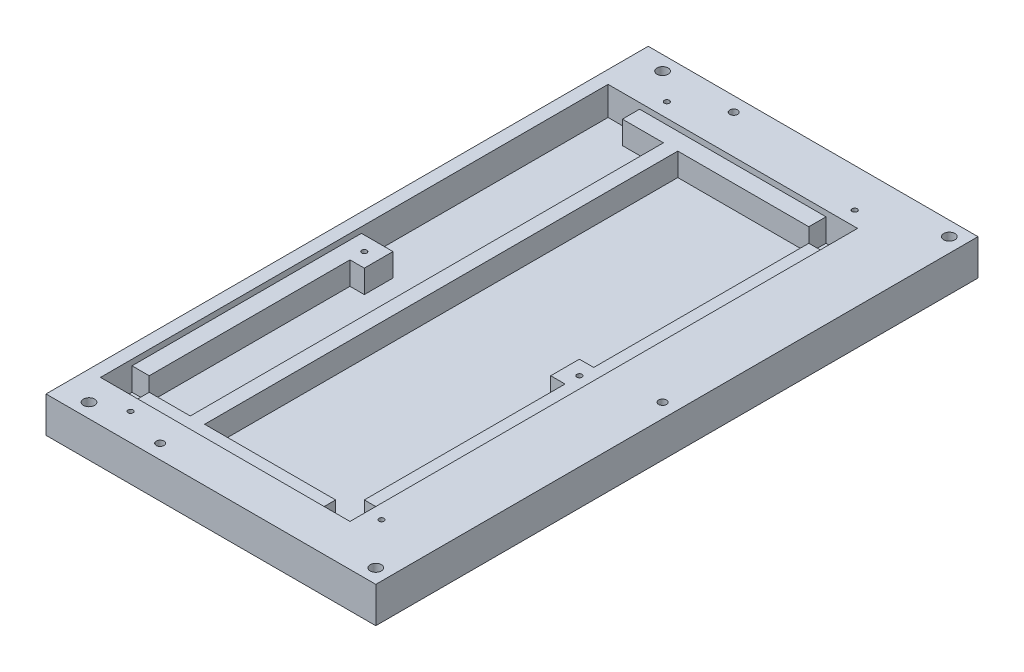
SolidWorks part; units mm, degrees
ref_plane "Front Plane" through (0, 0, 0) normal (0, 0, 1) x (1, 0, 0)
ref_plane "Top Plane" through (0, 0, 0) normal (0, 1, 0) x (1, 0, 0)
ref_plane "Right Plane" through (0, 0, 0) normal (1, 0, 0) x (0, 0, -1)
sketch "Sketch1" plane through (0, 0, 0) normal (0, 1, 0) x (1, 0, 0)
  line L1 (0, 0) -> (146.05, 0)
  line L2 (0, 0) -> (0, 266.7)
  line L3 (0, 266.7) -> (146.05, 266.7)
  line L4 (146.05, 0) -> (146.05, 266.7)
  dimension "D1" = 266.7
  dimension "D2" = 146.05
extrude "Boss-Extrude1" add sketch "Sketch1" along normal blind 15.875
sketch "Sketch2" plane through (0, 15.875, 0) normal (0, 1, 0) x (1, 0, 0)
  line L1 (5.715, 243.205) -> (116.205, 243.205)
  line L2 (5.715, 243.205) -> (5.715, 18.415)
  line L3 (5.715, 18.415) -> (116.205, 18.415)
  line L4 (116.205, 243.205) -> (116.205, 18.415)
  line L5 (0, 0) -> (146.05, 0) construction
  line L6 (0, 266.7) -> (0, 0) construction
  dimension "D1" = 224.79
  dimension "D2" = 110.49
  dimension "D3" = 5.715
  dimension "D4" = 18.415
extrude "Cut-Extrude1" cut sketch "Sketch2" against normal blind 2.54
sketch "Sketch3" plane through (0, 13.335, 0) normal (0, 1, 0) x (1, 0, 0)
  line L0 (19.685, 26.035) -> (19.685, 18.415)
  line L1 (19.685, 243.205) -> (19.685, 235.585)
  line L2 (19.685, 235.585) -> (37.8587, 235.585)
  line L3 (44.2087, 26.035) -> (102.235, 26.035)
  line L4 (102.235, 26.035) -> (102.235, 18.415)
  line L5 (44.2087, 235.585) -> (102.235, 235.585)
  line L6 (108.585, 32.385) -> (108.585, 121.285)
  line L7 (102.235, 235.585) -> (102.235, 243.205)
  line L8 (108.585, 121.285) -> (102.235, 121.285)
  line L9 (102.235, 121.285) -> (102.235, 133.985)
  line L10 (102.235, 133.985) -> (108.585, 133.985)
  line L11 (108.585, 133.985) -> (108.585, 229.235)
  line L12 (102.235, 243.205) -> (116.205, 243.205)
  line L13 (116.205, 243.205) -> (5.715, 243.205) construction
  line L14 (102.235, 18.415) -> (116.205, 18.415)
  line L15 (116.205, 18.415) -> (116.205, 32.385)
  line L16 (116.205, 18.415) -> (116.205, 243.205) construction
  line L17 (116.205, 32.385) -> (108.585, 32.385)
  line L18 (19.685, 243.205) -> (5.715, 243.205)
  line L19 (5.715, 243.205) -> (5.715, 18.415) construction
  line L20 (5.715, 243.205) -> (5.715, 133.985)
  line L22 (19.685, 18.415) -> (5.715, 18.415)
  line L23 (5.715, 243.205) -> (5.715, 18.415) construction
  line L24 (13.335, 121.285) -> (13.335, 32.385)
  line L25 (5.715, 18.415) -> (5.715, 32.385)
  line L26 (19.685, 26.035) -> (37.8587, 26.035)
  line L27 (37.8587, 235.585) -> (37.8587, 26.035)
  line L28 (116.205, 243.205) -> (116.205, 229.235)
  line L29 (44.2087, 26.035) -> (44.2087, 235.585)
  line L30 (116.205, 229.235) -> (108.585, 229.235)
  line L31 (5.715, 18.415) -> (116.205, 18.415) construction
  line L32 (5.715, 18.415) -> (116.205, 18.415) construction
  line L33 (5.715, 32.385) -> (13.335, 32.385)
  line L34 (5.715, 133.985) -> (19.685, 133.985)
  line L35 (116.205, 18.415) -> (116.205, 243.205) construction
  line L36 (19.685, 133.985) -> (19.685, 121.285)
  line L37 (19.685, 121.285) -> (13.335, 121.285)
  dimension "D3" = 7.62
  dimension "D4" = 13.97
  dimension "D5" = 6.35
  dimension "D6" = 13.97
  dimension "D7" = 13.97
  dimension "D8" = 13.97
  dimension "D9" = 12.7
  dimension "D10" = 12.7
  dimension "D11" = 88.9
  dimension "D12" = 18.1737
  dimension "D13" = 13.97
  dimension "D14" = 58.0263
  dimension "D15" = 13.97
  dimension "D16" = 6.35
  dimension "D17" = 7.62
  dimension "D18" = 7.62
  dimension "D19" = 7.62
  dimension "D20" = 6.35
  dimension "D21" = 6.35
  dimension "D22" = 13.97
  dimension "D23" = 88.9
  dimension "D24" = 7.62
  dimension "D25" = 7.62
  dimension "D26" = 209.55
  dimension "D27" = 95.25
extrude "Cut-Extrude2" cut sketch "Sketch3" against normal blind 10.16
hole_wizard "#4-40 Tapped Hole1" positions "Sketch5" profile "Sketch4" tap size "#4-40" standard "ANSI Inch"
sketch "Sketch5" plane through (0, 13.335, 0) normal (0, 1, 0) x (1, 0, 0)
  line L2 (102.235, 121.285) -> (102.235, 133.985) construction
  line L17 (108.585, 121.285) -> (102.235, 121.285) construction
  line L18 (19.685, 121.285) -> (13.335, 121.285) construction
  line L19 (19.685, 133.985) -> (19.685, 121.285) construction
  point P2 (108.585, 127.635)
  point P53 (13.335, 127.635)
  point P56 (16.51, 121.285)
  dimension "D1" = 6.35
  dimension "D2" = 6.35
  dimension "D3" = 6.35
  dimension "D4" = 6.35
sketch "Sketch4" plane through (108.585, 13.335, -127.635) normal (1, 0, 0) x (0, 0, 1)
  line L0 (0, 0) -> (0, 10.8392)
  line L1 (0, 10.8392) -> (1.1303, 10.16)
  line L2 (1.1303, 10.16) -> (1.1303, 0)
  line L5 (1.1303, 0) -> (0, 0)
  line L10 (0, 10.8392) -> (-1.1303, 10.16) construction
  line L11 (0, -6.35) -> (0, 107.95) construction
  dimension "Tap Drill Dia." = 2.2606
  dimension "Tap Drill Depth" = 10.16
  dimension "Drill Angle" = 118
cosmetic thread "Hole Thread5" parameters "D1"=5.6896, "D2"=2.8448
cosmetic thread "Hole Thread14" parameters "D1"=5.6896, "D2"=2.8448
hole_wizard "#8 Clearance Hole1" positions "Sketch9" profile "Sketch8" hole size "#8" standard "ANSI Inch" end condition through all
sketch "Sketch9" plane through (0, 15.875, 0) normal (0, 1, 0) x (1, 0, 0)
  line L0 (0, 0) -> (146.05, 0) construction
  line L1 (146.05, 0) -> (146.05, 266.7) construction
  line L2 (146.05, 266.7) -> (0, 266.7) construction
  line L3 (0, 266.7) -> (0, 0) construction
  point P0 (12.7, 6.35)
  point P2 (139.7, 6.35)
  point P4 (139.7, 260.35)
  point P6 (12.7, 260.35)
  dimension "D1" = 6.35
  dimension "D2" = 6.35
  dimension "D3" = 6.35
  dimension "D4" = 6.35
  dimension "D5" = 6.35
  dimension "D6" = 6.35
  dimension "D7" = 12.7
  dimension "D8" = 12.7
sketch "Sketch8" plane through (12.7, 15.875, -6.35) normal (1, 0, 0) x (0, 0, 1)
  line L0 (0, 0) -> (0, 15.875)
  line L1 (0, 15.875) -> (2.4574, 15.875)
  line L2 (2.4574, 15.875) -> (2.4574, 0)
  line L5 (2.4574, 0) -> (0, 0)
  line L11 (0, -6.35) -> (0, 107.95) construction
  dimension "Thru Hole Dia." = 4.9149
  dimension "Thru Hole Depth" = 15.875
hole_wizard "#8-32 Tapped Hole1" positions "Sketch11" profile "Sketch12" tap size "#8-32" standard "ANSI Inch"
sketch "Sketch11" plane through (0, 15.875, 0) normal (0, 1, 0) x (1, 0, 0)
  line L0 (37.8587, 26.035) -> (37.8587, 235.585) construction
  line L1 (146.05, 266.7) -> (0, 266.7) construction
  line L2 (0, 0) -> (146.05, 0) construction
  line L3 (146.05, 0) -> (146.05, 266.7) construction
  point P0 (44.2087, 6.35)
  point P2 (44.2087, 260.35)
  point P11 (139.7, 133.35)
  dimension "D1" = 6.35
  dimension "D2" = 6.35
  dimension "D3" = 6.35
  dimension "D4" = 6.35
  dimension "D5" = 6.35
  dimension "D6" = 133.35
  dimension "D7" = 133.35
cosmetic thread "Hole Thread7" parameters "D1"=8.3312, "D2"=4.1656
cosmetic thread "Hole Thread8" parameters "D1"=8.3312, "D2"=4.1656
cosmetic thread "Hole Thread9" parameters "D1"=8.3312, "D2"=4.1656
sketch "Sketch12" plane through (44.2087, 15.875, -6.35) normal (1, 0, 0) x (0, 0, 1)
  line L0 (0, 0) -> (0, 13.7378)
  line L1 (0, 13.7378) -> (1.7272, 12.7)
  line L2 (1.7272, 12.7) -> (1.7272, 0)
  line L5 (1.7272, 0) -> (0, 0)
  line L10 (0, 13.7378) -> (-1.7272, 12.7) construction
  line L11 (0, -6.35) -> (0, 107.95) construction
  dimension "Tap Drill Dia." = 3.4544
  dimension "Tap Drill Depth" = 12.7
  dimension "Drill Angle" = 118
hole_wizard "#4-40 Tapped Hole2" positions "Sketch14" profile "Sketch15" tap size "#4-40" standard "ANSI Inch"
sketch "Sketch14" plane through (0, 15.875, 0) normal (0, 1, 0) x (1, 0, 0)
  line L0 (116.205, 18.415) -> (116.205, 243.205) construction
  line L1 (116.205, 243.205) -> (5.715, 243.205) construction
  line L2 (5.715, 18.415) -> (116.205, 18.415) construction
  line L3 (0, 266.7) -> (0, 0) construction
  line L4 (102.235, 243.205) -> (102.235, 235.585) construction
  line L5 (116.205, 32.385) -> (108.585, 32.385) construction
  point P0 (108.585, 249.555)
  point P2 (122.555, 26.035)
  point P11 (25.4, 249.555)
  point P13 (25.4, 12.065)
  dimension "D1" = 6.35
  dimension "D2" = 6.35
  dimension "D3" = 6.35
  dimension "D4" = 6.35
  dimension "D5" = 6.35
  dimension "D6" = 6.35
  dimension "D7" = 25.4
  dimension "D8" = 25.4
sketch "Sketch15" plane through (108.585, 15.875, -249.555) normal (1, 0, 0) x (0, 0, 1)
  line L0 (0, 0) -> (0, 10.8392)
  line L1 (0, 10.8392) -> (1.1303, 10.16)
  line L2 (1.1303, 10.16) -> (1.1303, 0)
  line L5 (1.1303, 0) -> (0, 0)
  line L10 (0, 10.8392) -> (-1.1303, 10.16) construction
  line L11 (0, -6.35) -> (0, 107.95) construction
  dimension "Tap Drill Dia." = 2.2606
  dimension "Tap Drill Depth" = 10.16
  dimension "Drill Angle" = 118
cosmetic thread "Hole Thread10" parameters "D1"=5.6896, "D2"=2.8448
cosmetic thread "Hole Thread11" parameters "D1"=5.6896, "D2"=2.8448
cosmetic thread "Hole Thread12" parameters "D1"=5.6896, "D2"=2.8448
cosmetic thread "Hole Thread13" parameters "D1"=5.6896, "D2"=2.8448
